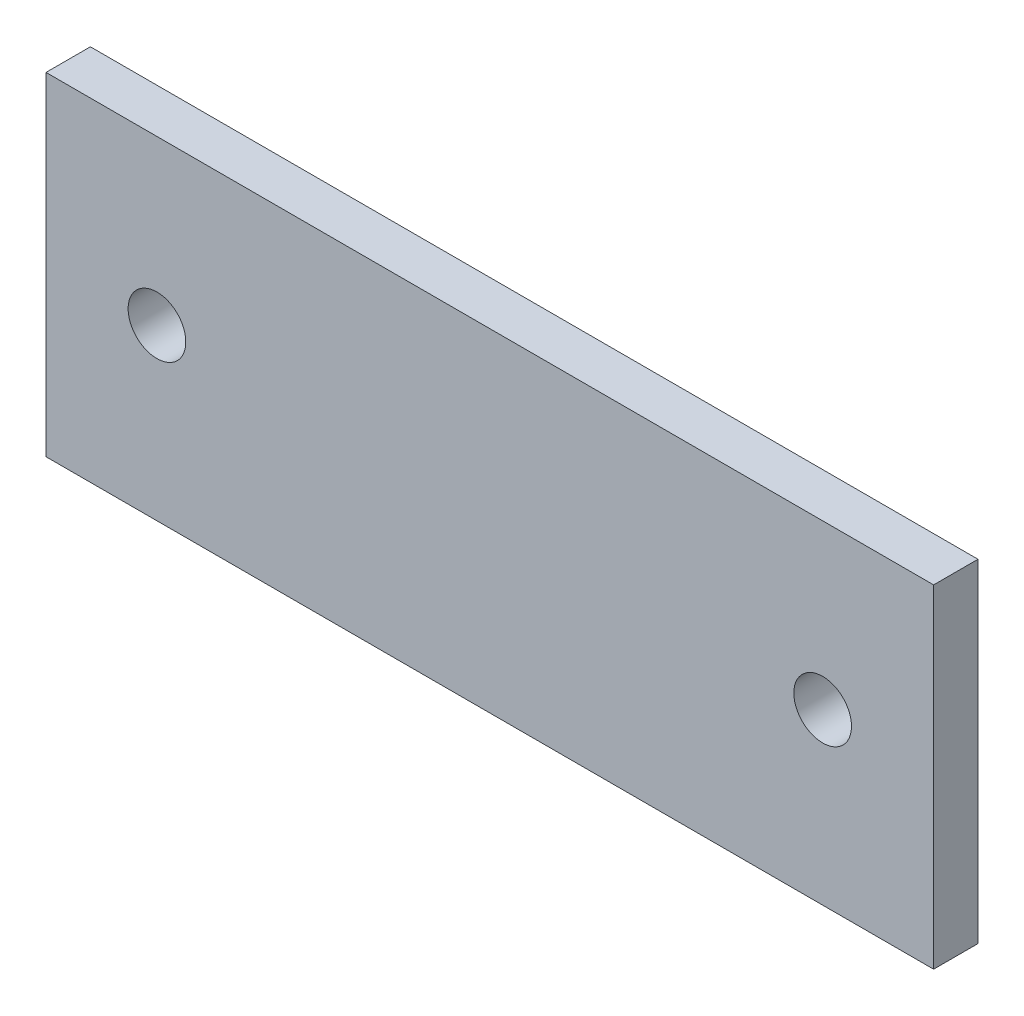
SolidWorks part; units mm, degrees
ref_plane "Front Plane" through (0, 0, 0) normal (0, 0, 1) x (1, 0, 0)
ref_plane "Top Plane" through (0, 0, 0) normal (0, 1, 0) x (1, 0, 0)
ref_plane "Right Plane" through (0, 0, 0) normal (1, 0, 0) x (0, 0, -1)
sketch "Sketch1" plane through (0, 0, 0) normal (0, 0, 1) x (1, 0, 0)
  line L1 (0, 0) -> (400, 0)
  line L2 (0, 0) -> (0, 150)
  line L3 (0, 150) -> (400, 150)
  line L4 (400, 0) -> (400, 150)
  circle A0 centre (50, 76.3007) radius 13
  circle A1 centre (350, 76.3007) radius 13
  dimension "D4" = 26
  dimension "Width" = 150
  dimension "Length" = 400
  dimension "D3" = 50
  dimension "D5" = 50
extrude "Extrude1" add sketch "Sketch1" along normal blind 20
